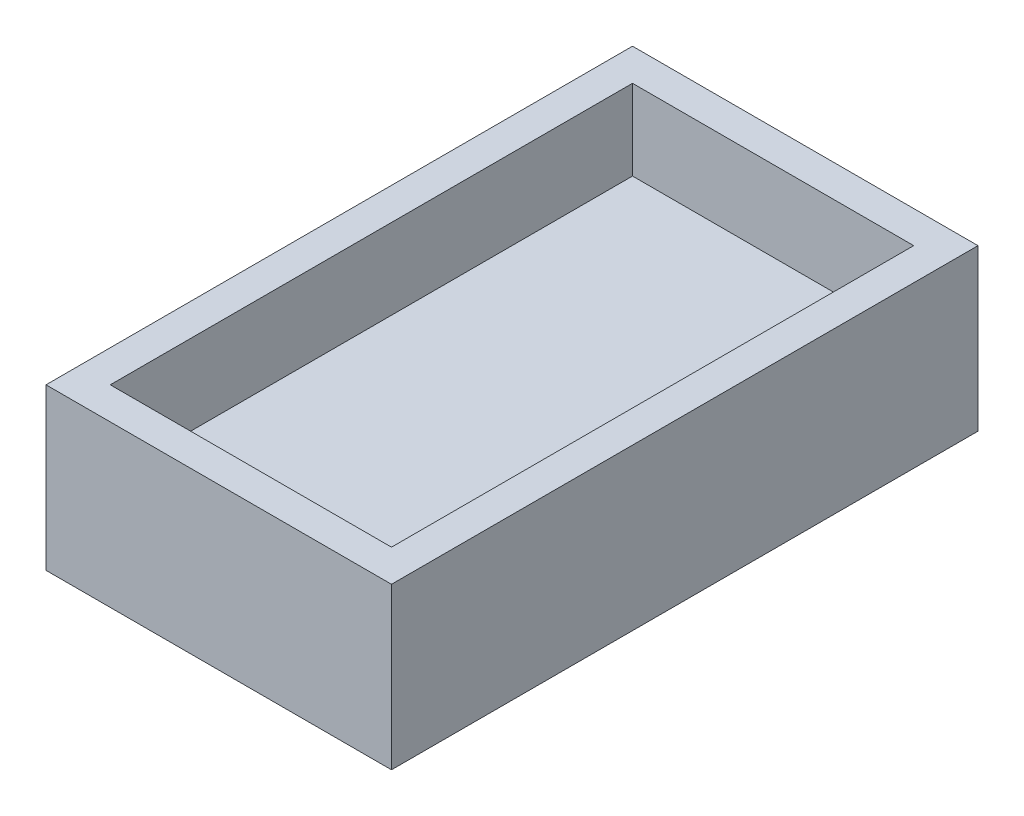
SolidWorks part; units mm, degrees
ref_plane "Front Plane" through (0, 0, 0) normal (0, 0, 1) x (1, 0, 0)
ref_plane "Top Plane" through (0, 0, 0) normal (0, 1, 0) x (1, 0, 0)
ref_plane "Right Plane" through (0, 0, 0) normal (1, 0, 0) x (0, 0, -1)
sketch "Sketch1" plane through (0, 0, 0) normal (0, 1, 0) x (1, 0, 0)
  line L0 (42.0793, 22.2422) -> (42.0793, -19.0328)
  line L1 (42.0793, 22.2422) -> (19.8543, 22.2422)
  line L2 (19.8543, 22.2422) -> (19.8543, -19.0328)
  line L3 (19.8543, -19.0328) -> (42.0793, -19.0328)
  line L4 (44.6193, 24.7822) -> (44.6193, -21.5728)
  line L5 (17.3143, -21.5728) -> (44.6193, -21.5728)
  line L6 (17.3143, 24.7822) -> (17.3143, -21.5728)
  line L7 (44.6193, 24.7822) -> (17.3143, 24.7822)
  dimension "D1" = 41.275
  dimension "D2" = 22.225
  dimension "D3" = 2.54
extrude "Boss-Extrude1" add sketch "Sketch1" against normal blind 6.35
sketch "Sketch3" plane through (0, -6.35, 0) normal (0, -1, 0) x (-1, 0, 0)
  line L1 (-17.3143, 24.7822) -> (-44.6193, 24.7822)
  line L2 (-17.3143, 24.7822) -> (-17.3143, -21.5728)
  line L3 (-17.3143, -21.5728) -> (-44.6193, -21.5728)
  line L4 (-44.6193, 24.7822) -> (-44.6193, -21.5728)
extrude "Boss-Extrude2" add sketch "Sketch3" along normal blind 6.35
sketch "Sketch4" plane through (0, -6.35, 0) normal (0, 1, 0) x (1, 0, 0)
  circle A0 centre (39.3958, 19.0931) radius 1.397
  circle A1 centre (39.3959, -15.7049) radius 1.397
  dimension "D1" = 2.794
  dimension "D3" = 2.794
  dimension "D2" = 36.195
extrude "Cut-Extrude1" cut sketch "Sketch4" against normal blind 6.35
